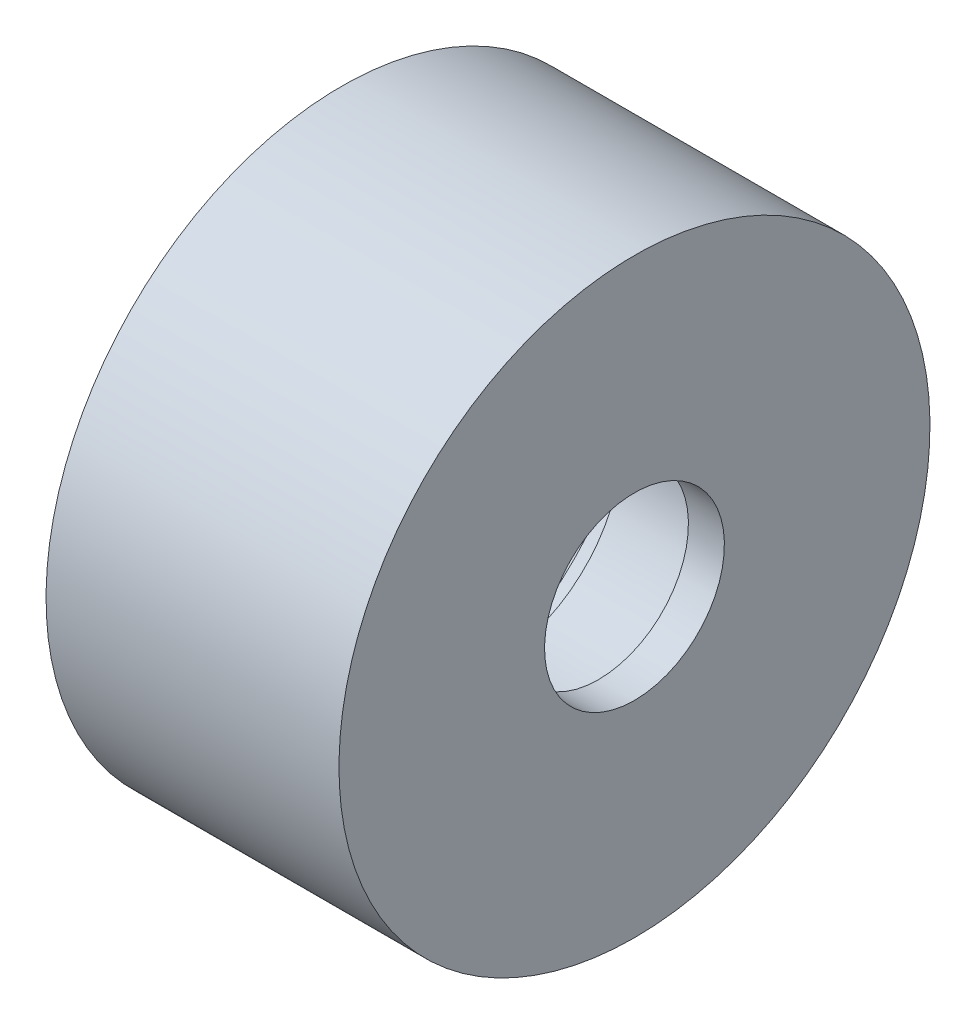
SolidWorks part; units mm, degrees
ref_plane "前视基准面" through (0, 0, 0) normal (0, 0, 1) x (1, 0, 0)
ref_plane "上视基准面" through (0, 0, 0) normal (0, 1, 0) x (1, 0, 0)
ref_plane "右视基准面" through (0, 0, 0) normal (1, 0, 0) x (0, 0, -1)
sketch "草图1" plane through (0, 0, 0) normal (0, 0, 1) x (1, 0, 0)
  line L0 (-19.1835, 2.5) -> (0.9247, 2.5) construction
  line L1 (-11.6, 6) -> (-11.6, 14)
  line L2 (-11.6, 14) -> (-23, 14)
  line L3 (-13, 6) -> (-13, 7.4)
  line L4 (-13, 7.4) -> (-17, 7.4)
  line L5 (-17, 7.4) -> (-17, 11)
  line L6 (-17, 11) -> (-20, 11)
  line L7 (-20, 11) -> (-20, 13)
  line L8 (-13, 6) -> (-11.6, 6)
  line L9 (-23, 12) -> (-20, 13)
  line L12 (-23, 12) -> (-23, 14)
  dimension "D1" = 8
  dimension "D2" = 4
  dimension "D3" = 3
  dimension "D4" = 2
  dimension "D5" = 2
  dimension "D6" = 1.4
  dimension "D7" = 3
  dimension "D8" = 1
revolve "旋转1" add sketch "草图1" angle 360 about L0
